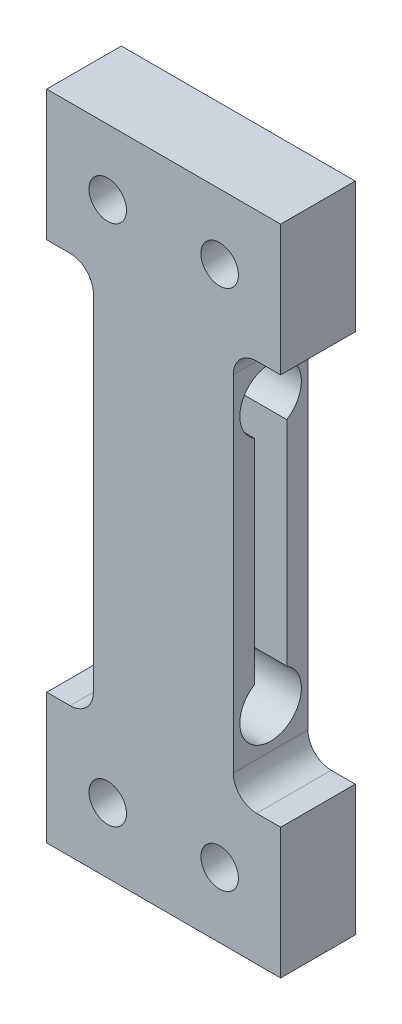
SolidWorks part; units mm, degrees
material "Acrilico TEC"
ref_plane "Front Plane" through (0, 0, 0) normal (0, 0, 1) x (1, 0, 0)
ref_plane "Top Plane" through (0, 0, 0) normal (0, 1, 0) x (1, 0, 0)
ref_plane "Right Plane" through (0, 0, 0) normal (1, 0, 0) x (0, 0, -1)
ref_plane "Plane1" through (0, 0, 0) normal (0, 0, -1) x (-1, 0, 0)
sketch "Sketch1" plane through (0, 0, 0) normal (0, 0, -1) x (-1, 0, 0)
  line L0 (-2.5384, 35) -> (-2.5384, 0)
  line L1 (-2.5384, 0) -> (10, 0)
  line L2 (10, 0) -> (10, 35)
  line L3 (10, 35) -> (-2.5384, 35)
extrude "Boss-Extrude1" add sketch "Sketch1" against normal blind 4
sketch "Sketch2" plane through (0, 0, 4) normal (0, 0, 1) x (1, 0, 0)
  line L0 (2.5384, 28) -> (0, 28)
  line L1 (0, 28) -> (0, 7)
  line L2 (0, 7) -> (2.5384, 7)
  line L3 (2.5384, 7) -> (2.5384, 28)
extrude "Cut-Extrude1" cut sketch "Sketch2" against normal through all
sketch "Sketch3" plane through (0, 0, 4) normal (0, 0, 1) x (1, 0, 0)
  line L0 (-10, 7) -> (-7.5, 7)
  line L1 (-7.5, 7) -> (-7.5, 28)
  line L2 (-7.5, 28) -> (-10, 28)
  line L3 (-10, 28) -> (-10, 7)
extrude "Cut-Extrude2" cut sketch "Sketch3" against normal through all
sketch "Sketch4" plane through (0, 0, 0) normal (1, 0, 0) x (0, 0, -1)
  line L0 (-2.8559, 23.2144) -> (-2.8559, 11.7856)
  line L1 (-1.1318, 11.7781) -> (-1.1318, 23.2219)
  arc A0 (-1.1318, 23.2219) -> (-2.8559, 23.2144) centre (-2, 24.625) cw
  arc A1 (-2.8559, 11.7856) -> (-1.1318, 11.7781) centre (-2, 10.375) cw
extrude "Cut-Extrude3" cut sketch "Sketch4" against normal through all
ref_plane "Plane2" through (0, 0, 2) normal (0, 0, 1) x (1, 0, 0)
sketch "Sketch5" plane through (0, 0, 2) normal (0, 0, 1) x (1, 0, 0)
  line L0 (-7.5, 12.025) -> (-7.5, 10.375)
  line L1 (-7.5, 10.375) -> (0, 10.375)
  line L2 (0, 10.375) -> (0, 12.025)
  line L3 (0, 12.025) -> (-7.5, 12.025)
  line L4 (-7.5, 10.375) -> (0, 10.375) construction
revolve "Cut-Revolve1" cut sketch "Sketch5" angle 360 about L4
sketch "Sketch6" plane through (0, 0, 2) normal (0, 0, 1) x (1, 0, 0)
  line L0 (-7.5, 26.275) -> (-7.5, 24.625)
  line L1 (-7.5, 24.625) -> (0, 24.625)
  line L2 (0, 24.625) -> (0, 26.275)
  line L3 (0, 26.275) -> (-7.5, 26.275)
  line L4 (-7.5, 24.625) -> (0, 24.625) construction
revolve "Cut-Revolve2" cut sketch "Sketch6" angle 360 about L4
hole_wizard "Hole1" positions "Sketch8" profile "Sketch7" legacy
sketch "Sketch8" plane through (0, 0, 0) normal (0, 0, -1) x (-1, 0, 0)
  point P0 (0.7308, 3.5)
  point P1 (6.7308, 3.5)
  point P2 (0.7308, 31.5)
  point P3 (6.7308, 31.5)
sketch "Sketch7" plane through (-0.7308, 3.5, 0) normal (1, 0, 0) x (0, 1, 0)
  line L0 (0, 0) -> (0, 4)
  line L1 (0, 4) -> (1.0065, 4)
  line L2 (1.0065, 4) -> (1.0065, 0)
  line L3 (1.0065, 0) -> (0, 0)
  line L4 (0, 110) -> (0, -10) construction
  dimension "Diameter" = 2.013
  dimension "Depth" = 4
fillet "Fillet1" radius 1.25 4 edges at (0, 28, 2) (0, 7, 2) (-7.5, 28, 2) (-7.5, 7, 2)
